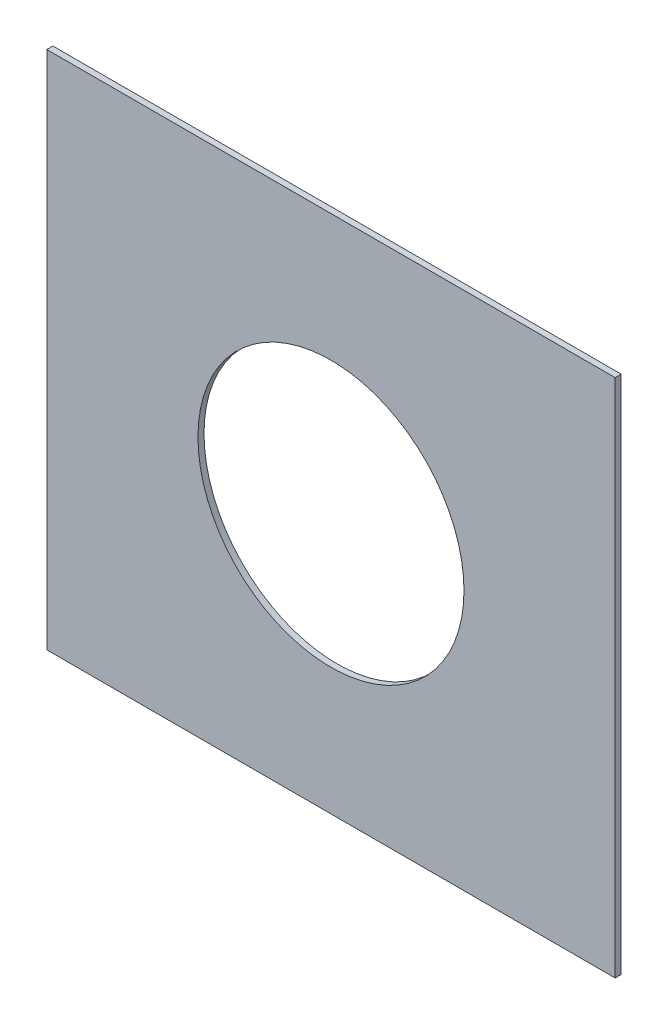
SolidWorks part; units mm, degrees
material "Al homeycomb"
ref_plane "Front Plane" through (0, 0, 0) normal (0, 0, 1) x (1, 0, 0)
ref_plane "Top Plane" through (0, 0, 0) normal (0, 1, 0) x (1, 0, 0)
ref_plane "Right Plane" through (0, 0, 0) normal (1, 0, 0) x (0, 0, -1)
sketch "Sketch1" plane through (0, 0, 0) normal (0, 0, 1) x (1, 0, 0)
  line L1 (-1175, -1075) -> (1175, -1075)
  line L2 (-1175, -1075) -> (-1175, 1075)
  line L3 (-1175, 1075) -> (1175, 1075)
  line L4 (1175, -1075) -> (1175, 1075)
  line L5 (-1175, -1075) -> (1175, 1075) construction
  line L6 (-1175, 1075) -> (1175, -1075) construction
  point P0 (0, 0)
  dimension "D1" = 2350
  dimension "D2" = 2150
extrude "Boss-Extrude1" add sketch "Sketch1" along normal blind 25
sketch "Sketch2" plane through (0, 0, 25) normal (0, 0, 1) x (1, 0, 0)
  circle A0 centre (0, 0) radius 550
  dimension "D1" = 1100
extrude "Cut-Extrude1" cut sketch "Sketch2" against normal up to surface (25 mm away) up to face at (0, 0, 0)
